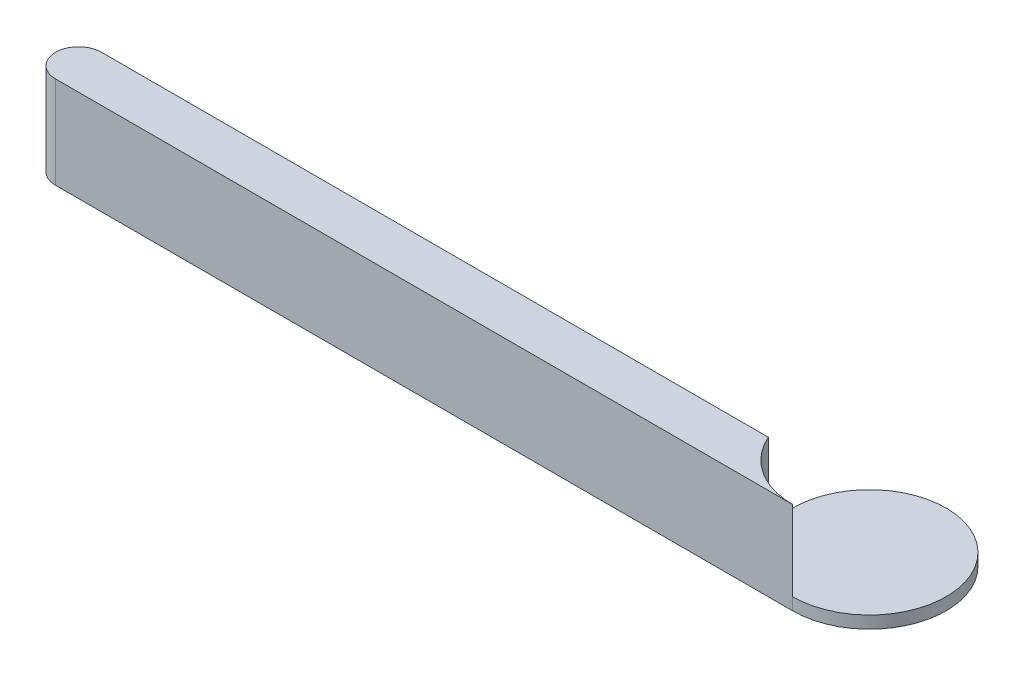
SolidWorks part; units mm, degrees
ref_plane "Front Plane" through (0, 0, 0) normal (0, 0, 1) x (1, 0, 0)
ref_plane "Top Plane" through (0, 0, 0) normal (0, 1, 0) x (1, 0, 0)
ref_plane "Right Plane" through (0, 0, 0) normal (1, 0, 0) x (0, 0, -1)
sketch "Sketch1" plane through (0, 0, 0) normal (0, 1, 0) x (1, 0, 0)
  line L1 (0, -4.7625) -> (152.4, -4.7625)
  line L3 (0, 4.7625) -> (137.8503, 4.7625)
  arc A0 (0, 4.7625) -> (0, -4.7625) centre (0, 0) ccw
  arc A1 (152.4, -4.7625) -> (137.8503, 4.7625) centre (152.4, 11.1125) ccw
  dimension "D1" = 9.525
  dimension "D3" = 31.75
  dimension "D2" = 152.4
extrude "Boss-Extrude1" add sketch "Sketch1" along normal blind 19.05
sketch "Sketch2" plane through (0, 19.05, 0) normal (0, 1, 0) x (1, 0, 0)
  circle A0 centre (152.4, 11.1125) radius 15.875
extrude "Cut-Extrude1" cut sketch "Sketch2" against normal blind 16.51
